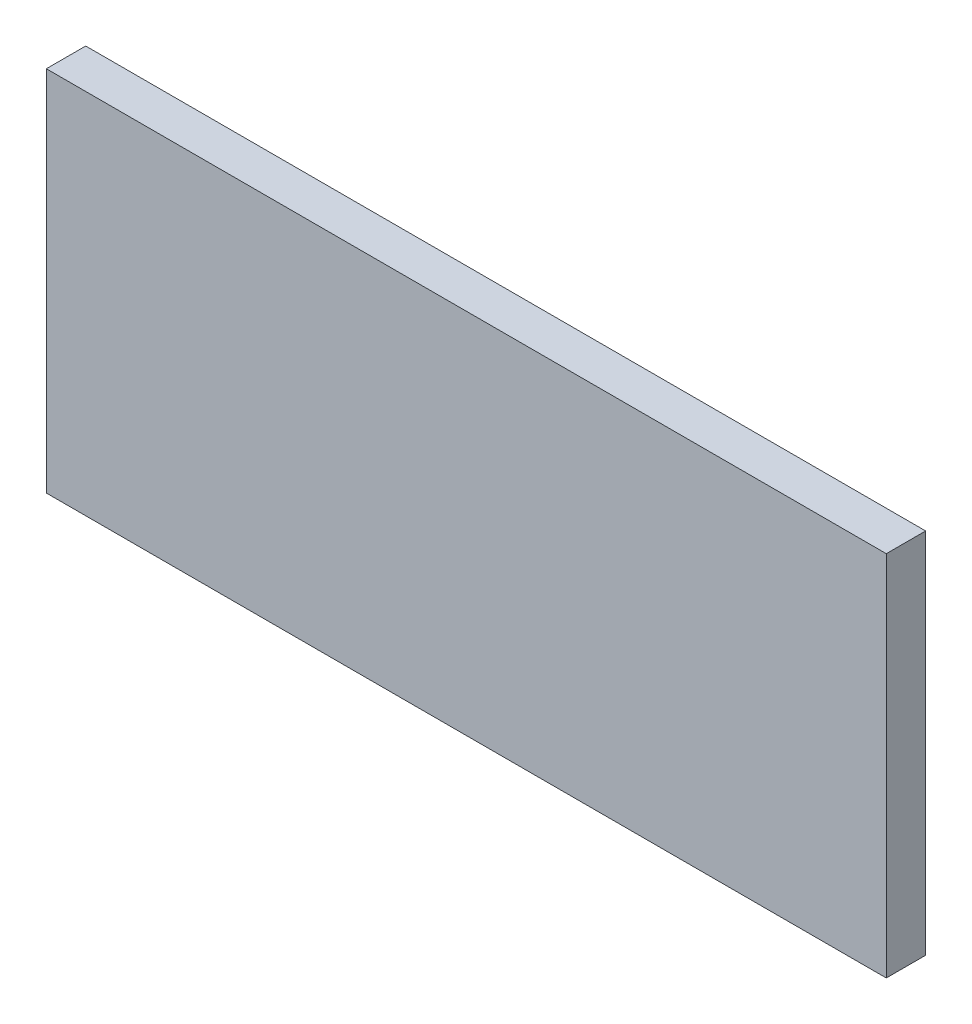
SolidWorks part; units mm, degrees
ref_plane "Plano frontal" through (0, 0, 0) normal (0, 0, 1) x (1, 0, 0)
ref_plane "Plano superior" through (0, 0, 0) normal (0, 1, 0) x (1, 0, 0)
ref_plane "Plano direito" through (0, 0, 0) normal (1, 0, 0) x (0, 0, -1)
sketch "Esboço1" plane through (0, 0, 0) normal (0, 0, 1) x (1, 0, 0)
  line L1 (-160, 70) -> (160, 70)
  line L2 (-160, 70) -> (-160, -70)
  line L3 (-160, -70) -> (160, -70)
  line L4 (160, 70) -> (160, -70)
  line L5 (-160, 70) -> (160, -70) construction
  line L6 (-160, -70) -> (160, 70) construction
  point P0 (0, 0)
  dimension "D1" = 140
  dimension "D2" = 320
extrude "Ressalto-extrusão1" add sketch "Esboço1" along normal blind 15
